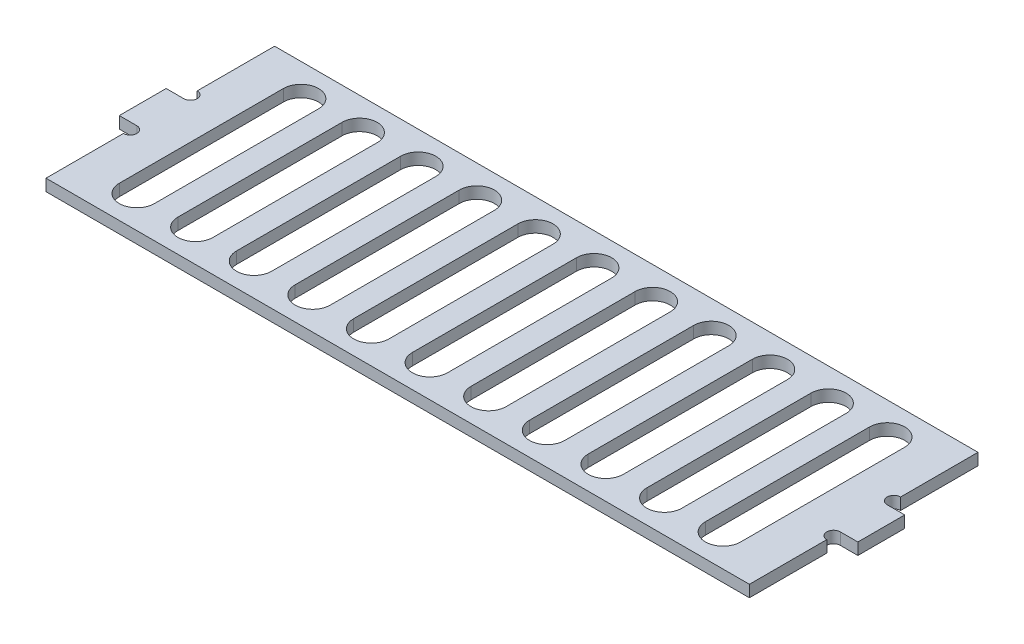
SolidWorks part; units mm, degrees
material "环氧树脂FR-4"
ref_plane "前视基准面" through (0, 0, 0) normal (0, 0, 1) x (1, 0, 0)
ref_plane "上视基准面" through (0, 0, 0) normal (0, 1, 0) x (1, 0, 0)
ref_plane "右视基准面" through (0, 0, 0) normal (1, 0, 0) x (0, 0, -1)
sketch "草图1" plane through (0, 0, 0) normal (0, 1, 0) x (1, 0, 0)
  line L1 (60, -19.5) -> (-60, -19.5)
  line L2 (60, -19.5) -> (60, 19.5)
  line L3 (60, 19.5) -> (-60, 19.5)
  line L4 (-60, -19.5) -> (-60, 19.5)
  line L5 (60, -19.5) -> (-60, 19.5) construction
  line L6 (60, 19.5) -> (-60, -19.5) construction
  point P0 (0, 0)
  dimension "D1" = 120
  dimension "D2" = 39
extrude "凸台-拉伸1" add sketch "草图1" along normal blind 2
sketch "草图2" plane through (-60, 0, 0) normal (-1, 0, 0) x (0, 0, 1)
  line L0 (-4, 0) -> (4, 0)
  line L1 (-19.5, 0) -> (19.5, 0) construction
  line L2 (4, 0) -> (4, 2)
  line L3 (-19.5, 2) -> (19.5, 2) construction
  line L4 (4, 2) -> (-4, 2)
  line L5 (-4, 2) -> (-4, 0)
  dimension "D1" = 8
extrude "凸台-拉伸2" add sketch "草图2" along normal blind 3
sketch "草图3" plane through (0, 2, 0) normal (0, 1, 0) x (1, 0, 0)
  line L0 (-60, 19.5) -> (-60, 4) construction
  line L1 (-60, -4) -> (-60, -19.5) construction
  circle A0 centre (-60, 5.15) radius 1.15
  circle A1 centre (-60, -5.15) radius 1.15
  dimension "D1" = 2.3
extrude "切除-拉伸1" cut sketch "草图3" against normal through all
mirror "镜向1" about plane through (0, 0, 0) normal (1, 0, 0) of "切除-拉伸1", "凸台-拉伸2"
sketch "草图4" plane through (0, 2, 0) normal (0, 1, 0) x (1, 0, 0)
  line L1 (3, -14) -> (-3, -14)
  line L2 (3, -14) -> (3, 14)
  line L3 (3, 14) -> (-3, 14)
  line L4 (-3, -14) -> (-3, 14)
  line L5 (3, -14) -> (-3, 14) construction
  line L6 (3, 14) -> (-3, -14) construction
  circle A0 centre (0, 14) radius 3
  circle A1 centre (0, -14) radius 3
  point P0 (0, 0)
  dimension "D2" = 6
  dimension "D1" = 28
extrude "切除-拉伸2" cut sketch "草图4" against normal through all contours A1 L2 A0 L4 | L3 A0 | L3 A0 | L1 A1 | L1 A1
pattern_linear "阵列(线性)1" count 6 spacing 10 along (-1, 0, 0) count 6 spacing 10 along (1, 0, 0) of "切除-拉伸2"
